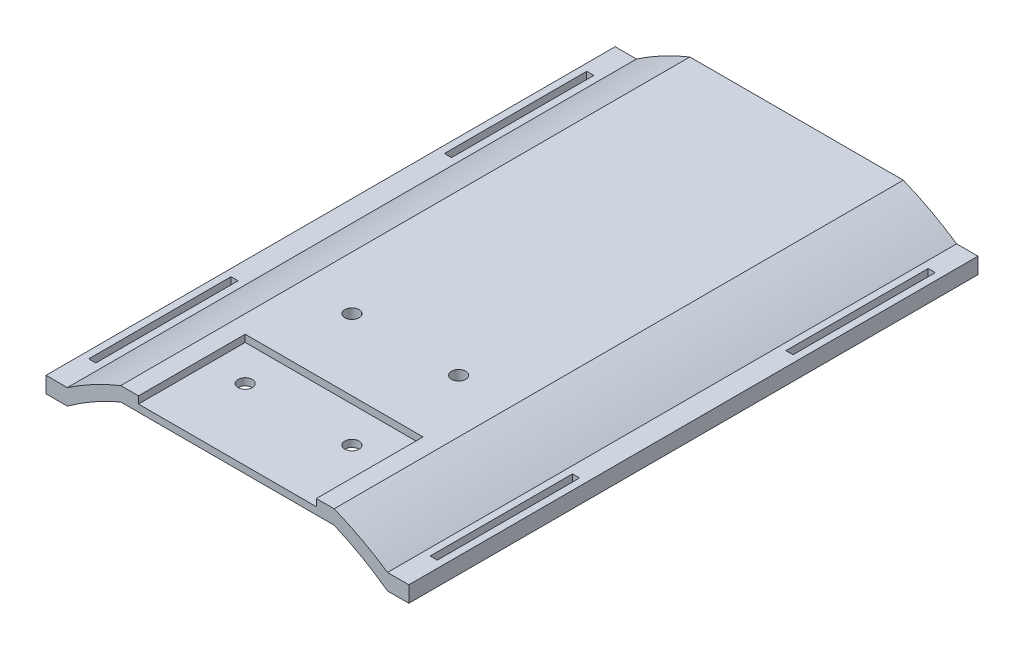
SolidWorks part; units mm, degrees
ref_plane "Front Plane" through (0, 0, 0) normal (0, 0, 1) x (1, 0, 0)
ref_plane "Top Plane" through (0, 0, 0) normal (0, 1, 0) x (1, 0, 0)
ref_plane "Right Plane" through (0, 0, 0) normal (1, 0, 0) x (0, 0, -1)
sketch "Sketch4" plane through (0, 0, 0) normal (0, 0, 1) x (1, 0, 0)
  line L6 (-19.1107, 53.8852) -> (-16.1107, 53.8852)
  line L7 (-8.6107, 57.8852) -> (21.3893, 57.8852)
  line L8 (28.8893, 53.8852) -> (31.8893, 53.8852)
  line L9 (-19.1107, 53.8852) -> (-19.1107, 51.6274)
  line L10 (-19.1107, 51.6274) -> (-16.1107, 51.6274)
  line L11 (-8.6107, 55.8852) -> (21.3893, 55.8852)
  line L12 (28.8893, 51.6274) -> (31.8893, 51.6274)
  line L13 (31.8893, 51.6274) -> (31.8893, 53.8852)
  arc A2 (-16.1107, 53.8852) -> (-8.6107, 57.8852) centre (6.3893, 20.729) cw
  arc A3 (28.8893, 53.8852) -> (21.3893, 57.8852) centre (6.3893, 20.729) ccw
  arc A4 (-16.1107, 51.6274) -> (-8.6107, 55.8852) centre (6.3893, 20.729) cw
  arc A5 (21.3893, 55.8852) -> (28.8893, 51.6274) centre (6.3893, 20.729) cw
  dimension "D11" = 30
  dimension "D3" = 7.5
  dimension "D6" = 7.5
  dimension "D1" = 3
  dimension "D2" = 4
  dimension "D4" = 30
  dimension "D5" = 4
  dimension "D7" = 3
  dimension "D8" = 2
  dimension "D9" = 7.5
  dimension "D10" = 3
  dimension "D12" = 7.5
  dimension "D13" = 3
  dimension "D14" = 2.2578
  dimension "D15" = 2.2578
extrude "Boss-Extrude1" add sketch "Sketch4" along normal blind 80
sketch "Sketch8" plane through (0, 57.8852, 0) normal (0, 1, 0) x (1, 0, 0)
  line L0 (21.3893, -80) -> (-8.6107, -80) construction
  line L1 (-6.1107, -80) -> (18.8893, -80)
  line L2 (-6.1107, -80) -> (-6.1107, -65)
  line L3 (-6.1107, -65) -> (18.8893, -65)
  line L4 (18.8893, -80) -> (18.8893, -65)
  line L5 (-8.6107, -80) -> (-8.6107, 0) construction
  dimension "D1" = 25
  dimension "D2" = 15
  dimension "D3" = 2.5
extrude "Cut-Extrude2" cut sketch "Sketch8" against normal blind 1
sketch "Sketch9" plane through (0, 56.8852, 0) normal (0, 1, 0) x (1, 0, 0)
  line L0 (-6.1107, -65) -> (-6.1107, -80) construction
  line L1 (18.8893, -65) -> (-6.1107, -65) construction
  line L2 (18.8893, -80) -> (18.8893, -65) construction
  circle A0 centre (-1.1107, -70) radius 1
  circle A1 centre (13.8893, -70) radius 1
  dimension "D1" = 5
  dimension "D2" = 5
  dimension "D3" = 5
  dimension "D4" = 5
extrude "Cut-Extrude3" cut sketch "Sketch9" against normal blind 1
ref_plane "Plane31" through (0, 51.63, 0) normal (0, 1, 0) x (1, 0, 0)
sketch "Sketch12" plane through (0, 53.8852, 0) normal (0, 1, 0) x (1, 0, 0)
  line L0 (-19.1107, -80) -> (-19.1107, 0) construction
  line L1 (-18.1107, -5) -> (-17.1107, -5)
  line L2 (-18.1107, -5) -> (-18.1107, -25)
  line L3 (-18.1107, -25) -> (-17.1107, -25)
  line L4 (-17.1107, -5) -> (-17.1107, -25)
  line L5 (-16.1107, 0) -> (-19.1107, 0) construction
  line L6 (-18.1107, -55) -> (-17.1107, -55)
  line L7 (-18.1107, -55) -> (-18.1107, -75)
  line L8 (-18.1107, -75) -> (-17.1107, -75)
  line L9 (-17.1107, -55) -> (-17.1107, -75)
  line L10 (-16.1107, -80) -> (-19.1107, -80) construction
  line L11 (-16.1107, -80) -> (-16.1107, 0) construction
  line L12 (29.8893, -5) -> (30.8893, -5)
  line L13 (29.8893, -5) -> (29.8893, -25)
  line L14 (29.8893, -25) -> (30.8893, -25)
  line L15 (30.8893, -5) -> (30.8893, -25)
  line L16 (29.8893, -55) -> (30.8893, -55)
  line L17 (29.8893, -55) -> (29.8893, -75)
  line L18 (29.8893, -75) -> (30.8893, -75)
  line L19 (30.8893, -55) -> (30.8893, -75)
  line L20 (31.8893, 0) -> (28.8893, 0) construction
  line L21 (28.8893, -80) -> (28.8893, 0) construction
  line L22 (31.8893, -80) -> (28.8893, -80) construction
  line L23 (31.8893, -80) -> (31.8893, 0) construction
  dimension "D1" = 1
  dimension "D2" = 1
  dimension "D3" = 20
  dimension "D4" = 5
  dimension "D5" = 5
  dimension "D6" = 20
  dimension "D7" = 1
  dimension "D8" = 1
  dimension "D9" = 5
  dimension "D10" = 1
  dimension "D11" = 5
  dimension "D12" = 1
  dimension "D13" = 1
  dimension "D14" = 1
  dimension "D15" = 20
  dimension "D16" = 20
extrude "Cut-Extrude4" cut sketch "Sketch12" against normal blind 4.69
sketch "Sketch13" plane through (0, 57.8852, 0) normal (0, 1, 0) x (1, 0, 0)
  circle A0 centre (-1.1107, -55) radius 1
  circle A1 centre (-1.1107, -70) radius 1 construction
  circle A2 centre (13.8893, -55) radius 1
  circle A3 centre (13.8893, -70) radius 1 construction
  dimension "D2" = 2
  dimension "D3" = 15
  dimension "D4" = 2
  dimension "D6" = 15
  dimension "D1" = 0
  dimension "D5" = 15
extrude "Cut-Extrude5" cut sketch "Sketch13" against normal blind 4.69
